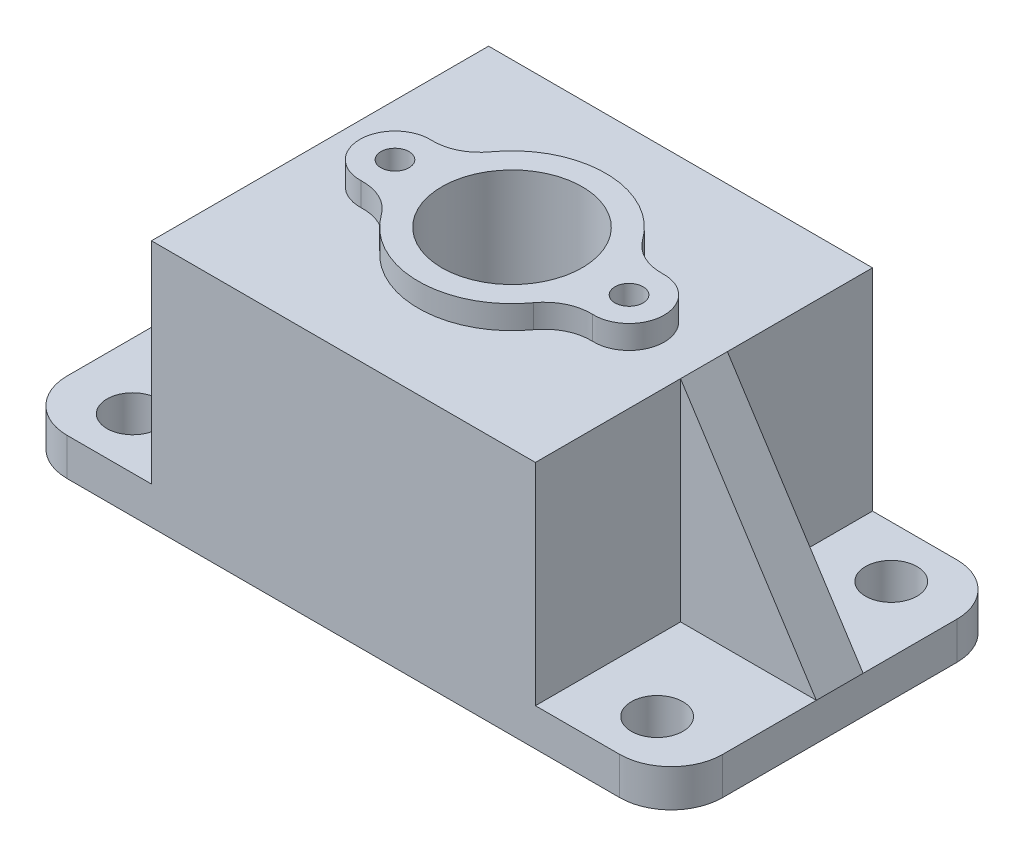
SolidWorks part; units mm, degrees
ref_plane "Front Plane" through (0, 0, 0) normal (0, 0, 1) x (1, 0, 0)
ref_plane "Top Plane" through (0, 0, 0) normal (0, 1, 0) x (1, 0, 0)
ref_plane "Right Plane" through (0, 0, 0) normal (1, 0, 0) x (0, 0, -1)
sketch "Sketch2" plane through (0, 0, 0) normal (0, 1, 0) x (1, 0, 0)
  line L1 (-59, -36) -> (59, -36)
  line L2 (-70, -25) -> (-70, 25)
  line L3 (-59, 36) -> (59, 36)
  line L4 (70, -25) -> (70, 25)
  line L5 (-70, -36) -> (70, 36) construction
  line L6 (-70, 36) -> (70, -36) construction
  circle A0 centre (-56, 25) radius 5.5
  circle A1 centre (-56, -25) radius 5.5
  circle A2 centre (56, 25) radius 5.5
  circle A3 centre (56, -25) radius 5.5
  arc A4 (59, 36) -> (70, 25) centre (59, 25) cw
  arc A5 (59, -36) -> (70, -25) centre (59, -25) ccw
  arc A6 (-59, -36) -> (-70, -25) centre (-59, -25) cw
  arc A7 (-70, 25) -> (-59, 36) centre (-59, 25) cw
  point P0 (0, 0)
  dimension "D4" = 11
  dimension "D5" = 11
  dimension "D15" = 11
  dimension "D1" = 140
  dimension "D2" = 72
  dimension "D7" = 11
  dimension "D8" = 11
  dimension "D9" = 11
  dimension "D10" = 11
  dimension "D11" = 112
  dimension "D12" = 56
  dimension "D13" = 112
  dimension "D14" = 56
extrude "Boss-Extrude1" add sketch "Sketch2" along normal blind 8
sketch "Sketch6" plane through (0, 8, 0) normal (0, 1, 0) x (1, 0, 0)
  line L0 (59, 36) -> (-59, 36) construction
  line L1 (-41, -36) -> (41, -36)
  line L2 (-41, -36) -> (-41, 36)
  line L3 (-41, 36) -> (41, 36)
  line L4 (41, -36) -> (41, 36)
  line L5 (-41, -36) -> (41, 36) construction
  line L6 (-41, 36) -> (41, -36) construction
  point P0 (0, 0)
  dimension "D1" = 82
extrude "Boss-Extrude4" add sketch "Sketch6" along normal blind 45
sketch "Sketch7" plane through (0, 53, 0) normal (0, 1, 0) x (1, 0, 0)
  line L0 (-70, 0) -> (70, 0) construction
  line L1 (-70, 25) -> (-70, -25) construction
  line L2 (70, -25) -> (70, 25) construction
  line L3 (0, 36) -> (0, -36) construction
  line L4 (41, 36) -> (-41, 36) construction
  line L5 (-41, -36) -> (41, -36) construction
  arc A0 (-16.25, -11.6592) -> (16.25, -11.6592) centre (0, 0) ccw
  arc A1 (-24.7321, 7.4952) -> (-24.7321, -7.4952) centre (-25, 0) ccw
  arc A2 (24.7321, -7.4952) -> (24.7321, 7.4952) centre (25, 0) ccw
  arc A3 (-24.7321, 7.4952) -> (-16.25, 11.6592) centre (-24.375, 17.4888) ccw
  arc A4 (-24.7321, -7.4952) -> (-16.25, -11.6592) centre (-24.375, -17.4888) cw
  arc A5 (16.25, 11.6592) -> (24.7321, 7.4952) centre (24.375, 17.4888) ccw
  arc A6 (16.25, 11.6592) -> (-16.25, 11.6592) centre (0, 0) ccw
  arc A7 (16.25, -11.6592) -> (24.7321, -7.4952) centre (24.375, -17.4888) cw
  dimension "D1" = 15
  dimension "D2" = 15
  dimension "D3" = 40
  dimension "D6" = 20
  dimension "D7" = 20
  dimension "D4" = 25
  dimension "D5" = 50
extrude "Boss-Extrude5" add sketch "Sketch7" along normal blind 5
sketch "Sketch8" plane through (0, 0, 0) normal (0, -1, 0) x (1, 0, 0)
  line L0 (-59, 36) -> (59, 36) construction
  line L1 (-26.5, -31.5) -> (26.5, -31.5)
  line L2 (-32.5, -25.5) -> (-32.5, 25.5)
  line L3 (-26.5, 31.5) -> (26.5, 31.5)
  line L4 (32.5, -25.5) -> (32.5, 25.5)
  line L5 (-32.5, -31.5) -> (32.5, 31.5) construction
  line L6 (-32.5, 31.5) -> (32.5, -31.5) construction
  arc A0 (-26.5, -31.5) -> (-32.5, -25.5) centre (-26.5, -25.5) cw
  arc A1 (26.5, -31.5) -> (32.5, -25.5) centre (26.5, -25.5) ccw
  arc A2 (26.5, 31.5) -> (32.5, 25.5) centre (26.5, 25.5) cw
  arc A3 (-32.5, 25.5) -> (-26.5, 31.5) centre (-26.5, 25.5) cw
  point P0 (0, 0)
  dimension "D3" = 6
  dimension "D1" = 65
  dimension "D2" = 4.5
extrude "Cut-Extrude1" cut sketch "Sketch8" against normal blind 35
fillet "Fillet1" radius 6 8 edges at (-30.7426, 35, -29.7426) (-32.5, 35, 0) (-30.7426, 35, 29.7426) (0, 35, 31.5) (30.7426, 35, 29.7426) (32.5, 35, 0) (30.7426, 35, -29.7426) (0, 35, -31.5)
sketch "Sketch9" plane through (0, 58, 0) normal (0, 1, 0) x (1, 0, 0)
  circle A0 centre (0, 0) radius 15
  circle A1 centre (25, 0) radius 3
  circle A2 centre (-25, 0) radius 3
  dimension "D1" = 30
  dimension "D2" = 6
  dimension "D3" = 6
extrude "Cut-Extrude2" cut sketch "Sketch9" against normal through all
sketch "Sketch11" plane through (0, 0, 0) normal (0, 0, 1) x (1, 0, 0)
  line L0 (-41, 53) -> (-70, 8)
rib "Rib2" sketch "Sketch11" sketch "Sketch11" thickness 10 extrusion direction parallel to sketch draft on no parameters "D1"=10
mirror "Mirror1" about plane through (0, 0, 0) normal (1, 0, 0) of "Rib2"
